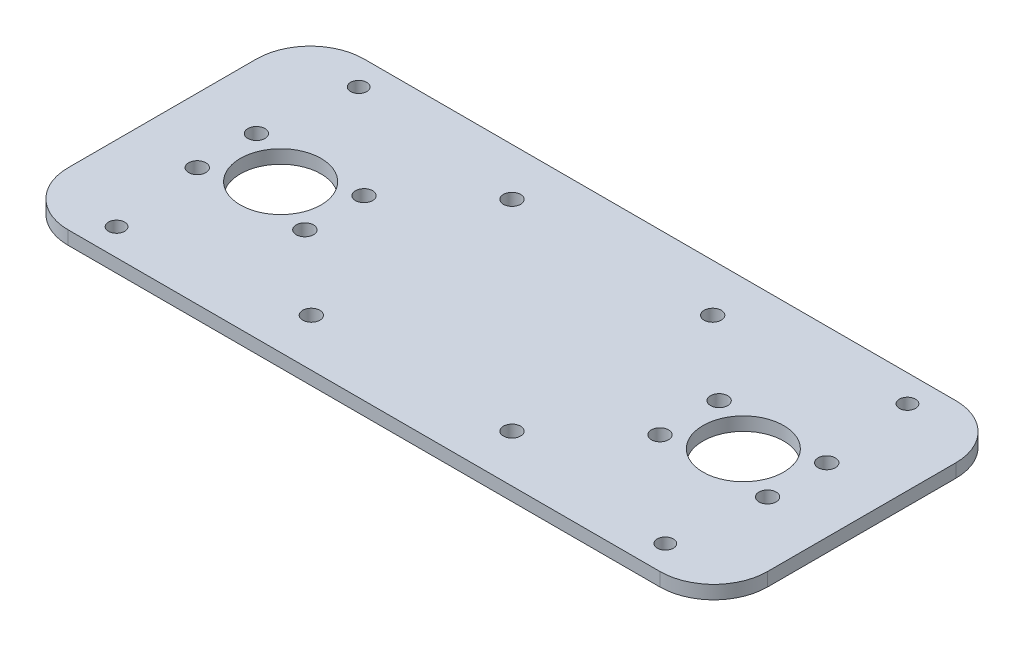
SolidWorks part; units mm, degrees
ref_plane "Front Plane" through (0, 0, 0) normal (0, 0, 1) x (1, 0, 0)
ref_plane "Top Plane" through (0, 0, 0) normal (0, 1, 0) x (1, 0, 0)
ref_plane "Right Plane" through (0, 0, 0) normal (1, 0, 0) x (0, 0, -1)
sketch "Sketch1" plane through (0, 0, 0) normal (0, 1, 0) x (1, 0, 0)
  line L1 (10, 0) -> (120, 0)
  line L2 (0, 10) -> (0, 45)
  line L3 (10, 55) -> (120, 55)
  line L4 (130, 10) -> (130, 45)
  arc A0 (10, 55) -> (0, 45) centre (10, 45) ccw
  arc A1 (0, 10) -> (10, 0) centre (10, 10) ccw
  arc A2 (130, 10) -> (120, 0) centre (120, 10) cw
  arc A3 (120, 55) -> (130, 45) centre (120, 45) cw
  point P7 (0, 55)
  point P10 (0, 0)
  point P13 (130, 0)
  dimension "D3" = 10
  dimension "D4" = 10
  dimension "D5" = 10
  dimension "D6" = 10
  dimension "D1" = 130
  dimension "D2" = 55
extrude "Boss-Extrude1" add sketch "Sketch1" along normal blind 2.5
sketch "Sketch2" plane through (0, 2.5, 0) normal (0, 1, 0) x (1, 0, 0)
  line L0 (0, 45) -> (0, 10) construction
  line L1 (10, 0) -> (120, 0) construction
  line L2 (120, 55) -> (10, 55) construction
  line L3 (65, 55) -> (65, 0) construction
  circle A0 centre (14, 5) radius 1.5
  circle A1 centre (14, 50) radius 1.5
  circle A2 centre (116, 5) radius 1.5
  circle A3 centre (116, 50) radius 1.5
  dimension "D1" = 3
  dimension "D4" = 3
  dimension "D2" = 14
  dimension "D3" = 5
  dimension "D5" = 5
extrude "Cut-Extrude1" cut sketch "Sketch2" against normal through all
sketch "Sketch3" plane through (0, 2.5, 0) normal (0, 1, 0) x (1, 0, 0)
  circle A0 centre (12, 33) radius 1.6
extrude "Cut-Extrude2" cut sketch "Sketch3" against normal blind 10
sketch "Sketch4" plane through (0, 2.5, 0) normal (0, 1, 0) x (1, 0, 0)
  circle A0 centre (12, 22) radius 1.6
extrude "Cut-Extrude3" cut sketch "Sketch4" against normal blind 10
sketch "Sketch5" plane through (0, 2.5, 0) normal (0, 1, 0) x (1, 0, 0)
  circle A0 centre (32, 33) radius 1.6
  circle A1 centre (32, 22) radius 1.6
extrude "Cut-Extrude4" cut sketch "Sketch5" against normal blind 10 contours A0 | A1
sketch "Sketch8" plane through (0, 2.5, 0) normal (0, 1, 0) x (1, 0, 0)
  circle A0 centre (98, 33) radius 1.6
  circle A1 centre (98, 22) radius 1.6
  circle A2 centre (118, 33) radius 1.6
  circle A3 centre (118, 22) radius 1.6
extrude "Cut-Extrude5" cut sketch "Sketch8" against normal blind 10
sketch "Sketch9" plane through (0, 2.5, 0) normal (0, 1, 0) x (1, 0, 0)
  circle A0 centre (46.35, 46.15) radius 1.6
  circle A1 centre (83.65, 46.15) radius 1.6
  circle A2 centre (83.65, 8.85) radius 1.6
  circle A3 centre (46.35, 8.85) radius 1.6
extrude "Cut-Extrude6" cut sketch "Sketch9" against normal blind 10
sketch "Sketch10" plane through (0, 0, 0) normal (0, -1, 0) x (1, 0, 0)
  line L0 (65, 0) -> (65, -55) construction
  line L1 (10, 0) -> (120, 0) construction
  line L2 (120, -55) -> (10, -55) construction
  circle A0 centre (22, -27.5) radius 7.5
  circle A1 centre (108, -27.5) radius 7.5
extrude "Cut-Extrude7" cut sketch "Sketch10" against normal blind 10
